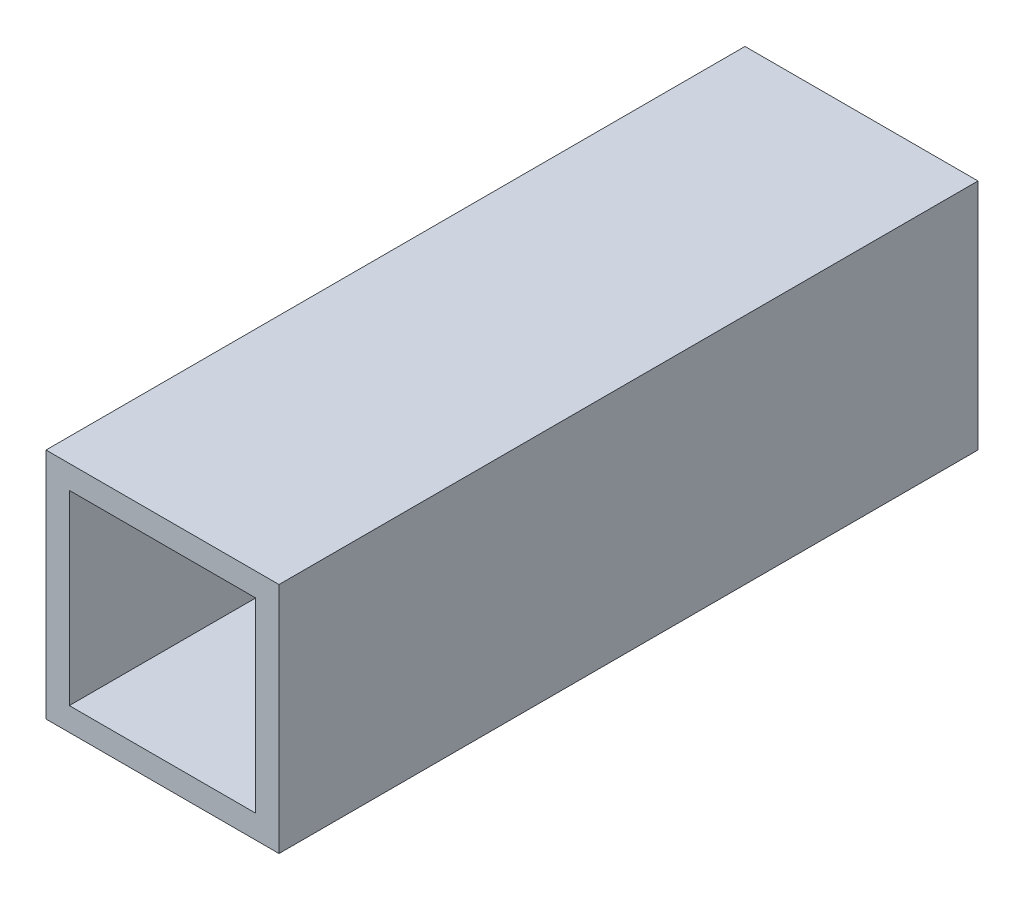
SolidWorks part; units mm, degrees
ref_plane "Front Plane" through (0, 0, 0) normal (0, 0, 1) x (1, 0, 0)
ref_plane "Top Plane" through (0, 0, 0) normal (0, 1, 0) x (1, 0, 0)
ref_plane "Right Plane" through (0, 0, 0) normal (1, 0, 0) x (0, 0, -1)
sketch "Sketch1" plane through (0, 0, 0) normal (0, 0, 1) x (1, 0, 0)
  line L0 (-20, 20) -> (-20, -20)
  line L1 (-25, 25) -> (25, 25)
  line L2 (-25, 25) -> (-25, -25)
  line L3 (-25, -25) -> (25, -25)
  line L4 (25, 25) -> (25, -25)
  line L5 (-20, -20) -> (20, -20)
  line L6 (20, 20) -> (20, -20)
  line L7 (-20, 20) -> (20, 20)
  dimension "tube_width" = 50
  dimension "D1" = 50
  dimension "D3" = 25
  dimension "D4" = 25
  dimension "tube_thickness" = 5
extrude "Boss-Extrude1" add sketch "Sketch1" along normal blind 150
sketch "Sketch2" plane through (0, 25, 0) normal (0, 1, 0) x (1, 0, 0)
  text T0 "<r180>z</r>" font "Century Gothic" height 40
  point P1 (0, 0)
  point P2 (0, 0)
  point P3 (0, 0)
  point P4 (0, 0)
  point P5 (0, 0)
  point P6 (0, 0)
  point P7 (0, 0)
  point P8 (17.0543, -107.3437)
equation "\"D1@Sketch1\"= \"tube_width@Sketch1\""
equation "\"D3@Sketch1\"=\"tube_width@Sketch1\"/2"
equation "\"D4@Sketch1\"=\"tube_width@Sketch1\"/2"
